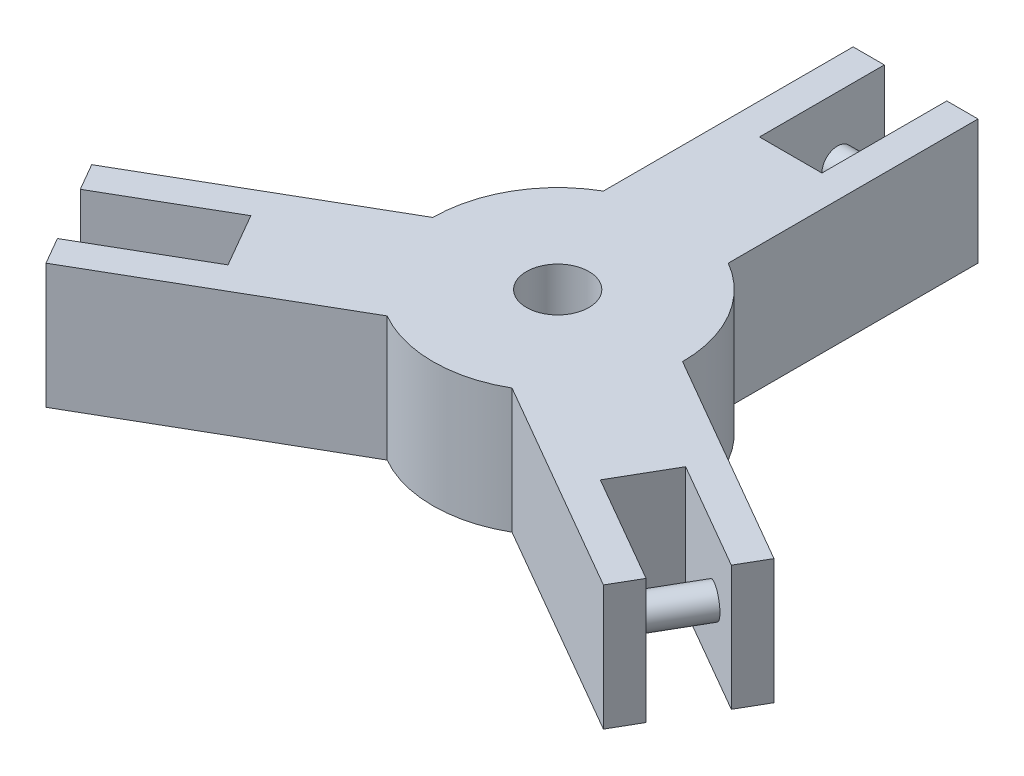
SolidWorks part; units mm, degrees
material "AISI 1020"
ref_plane "Front Plane" through (0, 0, 0) normal (0, 0, 1) x (1, 0, 0)
ref_plane "Top Plane" through (0, 0, 0) normal (0, 1, 0) x (1, 0, 0)
ref_plane "Right Plane" through (0, 0, 0) normal (1, 0, 0) x (0, 0, -1)
sketch "Sketch1" plane through (0, 0, 0) normal (0, 1, 0) x (1, 0, 0)
  line L1 (-20, 114.641) -> (-20, 34.641)
  line L2 (-20, 114.641) -> (-10, 114.641)
  line L3 (109.282, -40) -> (40, 0)
  line L4 (10, 114.641) -> (20, 114.641)
  line L5 (20, 114.641) -> (20, 34.641)
  line L6 (109.282, -40) -> (104.282, -48.6603)
  line L7 (10, 114.641) -> (10, 74.641)
  line L8 (10, 74.641) -> (-10, 74.641)
  line L9 (-10, 114.641) -> (-10, 74.641)
  line L10 (94.282, -65.9808) -> (89.282, -74.641)
  line L11 (89.282, -74.641) -> (20, -34.641)
  line L12 (94.282, -65.9808) -> (59.641, -45.9808)
  line L13 (59.641, -45.9808) -> (69.641, -28.6603)
  line L14 (104.282, -48.6603) -> (69.641, -28.6603)
  line L15 (-89.282, -74.641) -> (-20, -34.641)
  line L16 (-89.282, -74.641) -> (-94.282, -65.9808)
  line L17 (-104.282, -48.6603) -> (-109.282, -40)
  line L18 (-109.282, -40) -> (-40, 0)
  line L19 (-104.282, -48.6603) -> (-69.641, -28.6603)
  line L20 (-69.641, -28.6603) -> (-59.641, -45.9808)
  line L21 (-94.282, -65.9808) -> (-59.641, -45.9808)
  circle A0 centre (0, 0) radius 10
  circle A1 centre (0, 0) radius 40
  dimension "D1" = 80
  dimension "D2" = 20
  dimension "D3" = 20
  dimension "D4" = 40
  dimension "D5" = 80
  dimension "D6" = 40
  dimension "D7" = 3
extrude "Boss-Extrude1" add sketch "Sketch1" along normal blind 40
sketch "Sketch2" plane through (-10, 0, 0) normal (1, 0, 0) x (0, 0, -1)
  line L0 (114.641, 20) -> (99.641, 20) construction
  line L1 (114.641, 40) -> (114.641, 0) construction
  circle A0 centre (99.641, 20) radius 5
  dimension "D2" = 10
  dimension "D1" = 15
extrude "Boss-Extrude2" add sketch "Sketch2" along normal blind 25
pattern_circular "CirPattern1" count 3 over 360 about axis through (0, 40, 0) along (0, 1, 0) of "Boss-Extrude2"
